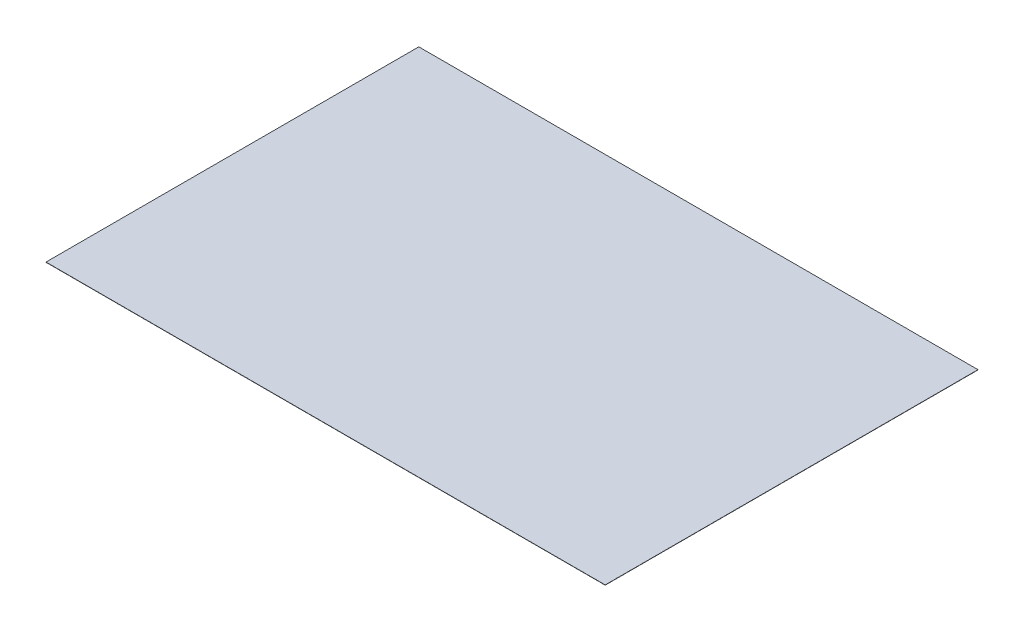
SolidWorks part; units mm, degrees
ref_plane "Front Plane" through (0, 0, 0) normal (0, 0, 1) x (1, 0, 0)
ref_plane "Top Plane" through (0, 0, 0) normal (0, 1, 0) x (1, 0, 0)
ref_plane "Right Plane" through (0, 0, 0) normal (1, 0, 0) x (0, 0, -1)
sketch "Sketch1" plane through (0, 0, 0) normal (0, 1, 0) x (1, 0, 0)
  line L1 (0, 0) -> (24000, 0)
  line L2 (0, 0) -> (0, 16000)
  line L3 (0, 16000) -> (24000, 16000)
  line L4 (24000, 0) -> (24000, 16000)
  dimension "D1" = 24000
  dimension "D2" = 16000
extrude "Boss-Extrude1" add sketch "Sketch1" along normal blind 10
sketch "Sketch2" plane through (0, 10, 0) normal (0, 1, 0) x (1, 0, 0)
  line L0 (0, 8000) -> (24000, 8000) construction
  line L1 (0, 16000) -> (0, 0) construction
  line L2 (24000, 0) -> (24000, 16000) construction
  line L3 (24000, 11983.8105) -> (0, 11983.8105) construction
  line L4 (0, 4046.3819) -> (24000, 4046.3819) construction
  line L5 (11919.1119, 16000) -> (12000, 0) construction
  line L6 (24000, 16000) -> (0, 16000) construction
  line L7 (0, 0) -> (24000, 0) construction
  line L8 (20169.6084, 16000) -> (20169.6084, 0) construction
  line L9 (3792.5548, 0) -> (3792.5548, 16000) construction
  point P20 (3792.5548, 4046.3819)
  point P21 (3792.5548, 11983.8105)
  point P22 (20169.6084, 11983.8105)
  point P23 (20169.6084, 8000)
  point P24 (20169.6084, 4046.3819)
  point P25 (12000, 8000)
  point P26 (11939.4158, 11983.8105)
  point P27 (3792.5548, 8000)
